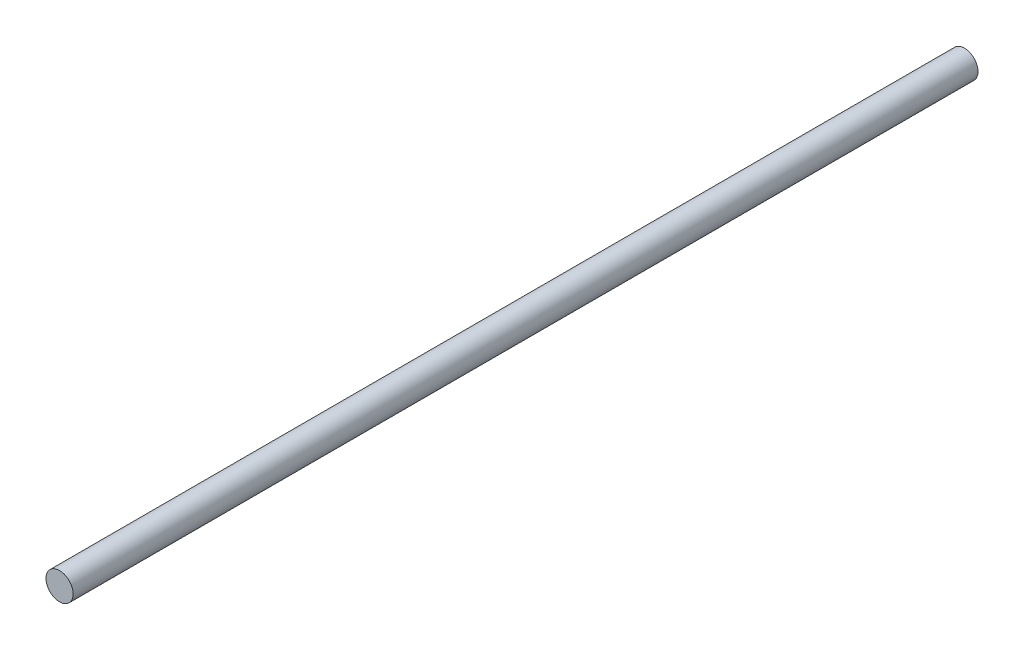
SolidWorks part; units mm, degrees
ref_plane "Ön Düzlem" through (0, 0, 0) normal (0, 0, 1) x (1, 0, 0)
ref_plane "Üst Düzlem" through (0, 0, 0) normal (0, 1, 0) x (1, 0, 0)
ref_plane "Sağ Düzlem" through (0, 0, 0) normal (1, 0, 0) x (0, 0, -1)
sketch "Çizim1" plane through (0, 0, 0) normal (0, 0, 1) x (1, 0, 0)
  circle A0 centre (0, 0) radius 6
  dimension "D1" = 12
extrude "Yükseklik-Ekstrüzyon1" add sketch "Çizim1" along normal blind 400
